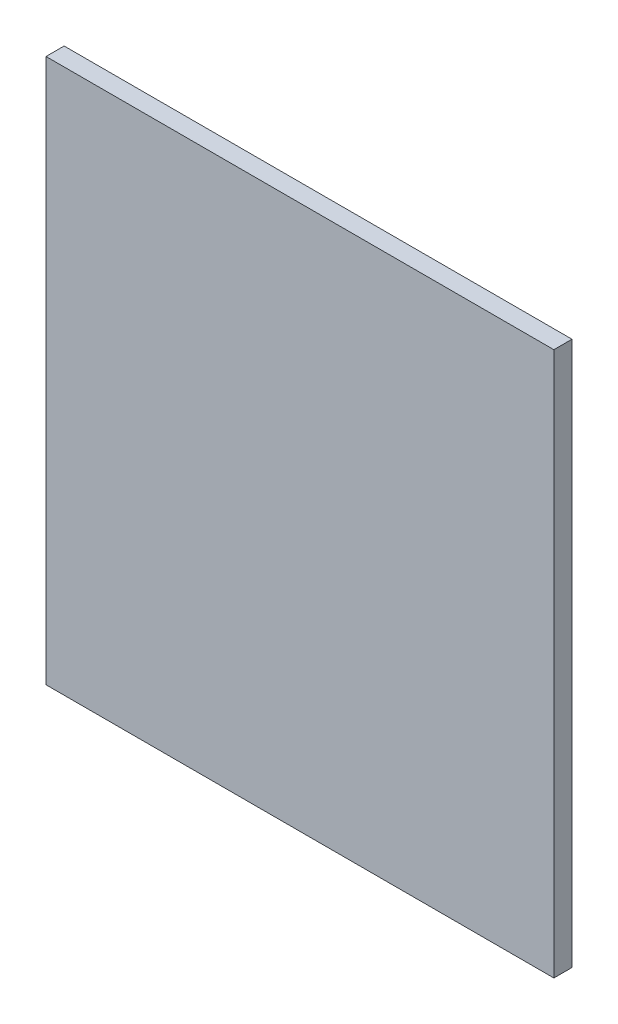
SolidWorks part; units mm, degrees
ref_plane "Front Plane" through (0, 0, 0) normal (0, 0, 1) x (1, 0, 0)
ref_plane "Top Plane" through (0, 0, 0) normal (0, 1, 0) x (1, 0, 0)
ref_plane "Right Plane" through (0, 0, 0) normal (1, 0, 0) x (0, 0, -1)
sketch "Sketch1" plane through (0, 0, 0) normal (0, 0, 1) x (1, 0, 0)
  line L1 (-44.2377, 27.7268) -> (26.8823, 27.7268)
  line L2 (-44.2377, 27.7268) -> (-44.2377, -48.4732)
  line L3 (-44.2377, -48.4732) -> (26.8823, -48.4732)
  line L4 (26.8823, 27.7268) -> (26.8823, -48.4732)
extrude "Boss-Extrude1" add sketch "Sketch1" along normal blind 2.54
